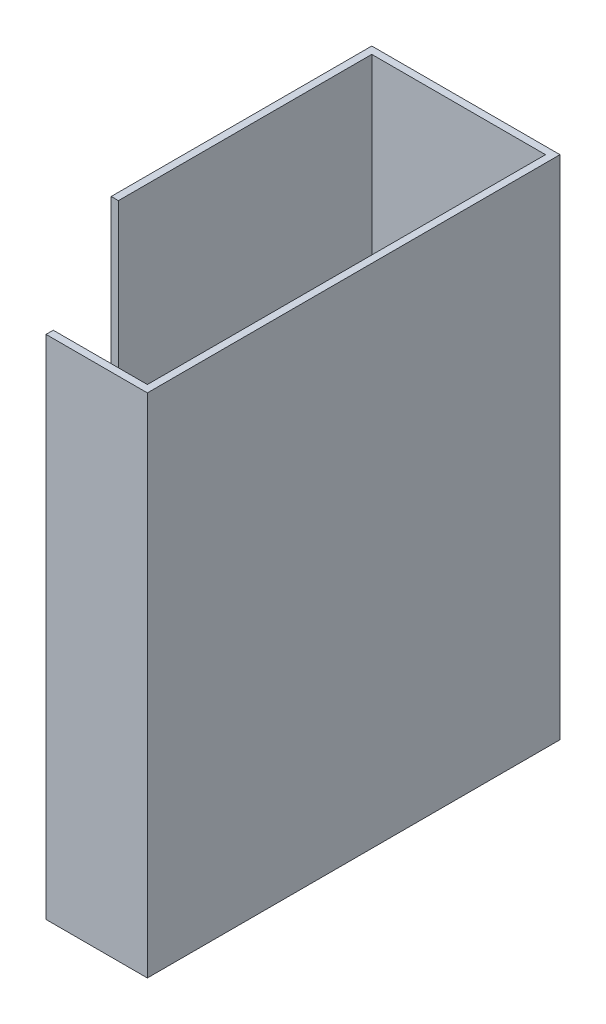
SolidWorks part; units mm, degrees
ref_plane "Front Plane" through (0, 0, 0) normal (0, 0, 1) x (1, 0, 0)
ref_plane "Top Plane" through (0, 0, 0) normal (0, 1, 0) x (1, 0, 0)
ref_plane "Right Plane" through (0, 0, 0) normal (1, 0, 0) x (0, 0, -1)
sketch "Sketch1" plane through (0, 0, 0) normal (0, 1, 0) x (1, 0, 0)
  line L0 (0, 0) -> (0, 570)
  line L1 (0, 570) -> (-260, 570)
  line L2 (-260, 570) -> (-260, 210)
  line L3 (-260, 210) -> (-250, 210)
  line L4 (-250, 210) -> (-250, 560)
  line L5 (-250, 560) -> (-10, 560)
  line L6 (-10, 560) -> (-10, 10)
  line L7 (-10, 10) -> (-140, 10)
  line L8 (-140, 10) -> (-140, 0)
  line L9 (-140, 0) -> (0, 0)
  dimension "D1" = 570
  dimension "D2" = 260
  dimension "D3" = 360
  dimension "D4" = 10
  dimension "D5" = 10
  dimension "D6" = 10
  dimension "D7" = 10
  dimension "D8" = 130
extrude "Boss-Extrude1" add sketch "Sketch1" along normal blind 700
